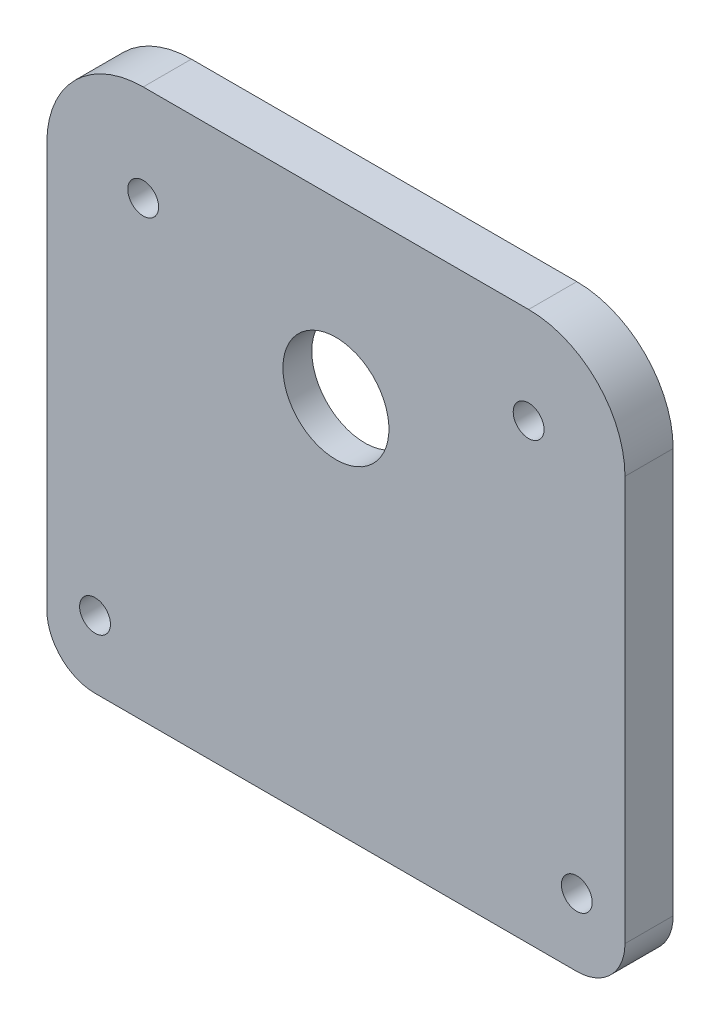
SolidWorks part; units mm, degrees
ref_plane "前视基准面" through (0, 0, 0) normal (0, 0, 1) x (1, 0, 0)
ref_plane "上视基准面" through (0, 0, 0) normal (0, 1, 0) x (1, 0, 0)
ref_plane "右视基准面" through (0, 0, 0) normal (1, 0, 0) x (0, 0, -1)
other "Configuration Table"
sketch "草图1" plane through (0, 0, 0) normal (0, 0, 1) x (1, 0, 0)
  line L1 (-30, -25) -> (30, -25)
  line L2 (-30, -25) -> (-30, 25)
  line L3 (-30, 25) -> (30, 25)
  line L4 (30, -25) -> (30, 25)
  line L5 (-30, -25) -> (30, 25) construction
  line L6 (-30, 25) -> (30, -25) construction
  circle A0 centre (0, 0) radius 15
  point P0 (0, 0)
  dimension "D3" = 30
  dimension "D1" = 60
  dimension "D2" = 50
extrude "凸台-拉伸5" add sketch "草图1" along normal blind 5
sketch "草图4" plane through (0, 0, 5) normal (0, 0, 1) x (1, 0, 0)
  line L1 (-30, -25) -> (30, -25)
  line L2 (-30, -25) -> (-30, 25)
  line L3 (-30, 25) -> (30, 25)
  line L4 (30, -25) -> (30, 25)
  line L5 (-30, -25) -> (30, 25) construction
  line L6 (-30, 25) -> (30, -25) construction
  circle A0 centre (0, 0) radius 5.5
  dimension "D1" = 11
extrude "凸台-拉伸6" add sketch "草图4" along normal blind 5
sketch "草图5" plane through (0, 0, 0) normal (0, 0, -1) x (-1, 0, 0)
  circle A0 centre (-20, 22) radius 1.6
  circle A1 centre (-25, -18) radius 1.6
  circle A2 centre (20, 22) radius 1.6
  circle A3 centre (25, -18) radius 1.6
extrude "切除-拉伸1" cut sketch "草图5" against normal blind 10
sketch "草图6" plane through (0, 25, 0) normal (0, 1, 0) x (1, 0, 0)
  line L1 (-30, -10) -> (30, -10)
  line L2 (-30, -10) -> (-30, 0)
  line L3 (-30, 0) -> (30, 0)
  line L4 (30, -10) -> (30, 0)
extrude "凸台-拉伸7" add sketch "草图6" along normal blind 7
fillet "圆角3" radius 10 1 edges at (-30, 32, 5)
fillet "圆角5" radius 10 1 edges at (30, 32, 5)
fillet "圆角6" radius 5 1 edges at (-30, -25, 5)
fillet "圆角7" radius 5 1 edges at (30, -25, 5)
sketch "草图7" plane through (0, 0, 0) normal (0, 0, -1) x (-1, 0, 0)
  line L1 (-30.7675, 32.3093) -> (32.1624, 32.3093)
  line L2 (-30.7675, 32.3093) -> (-30.7675, -27.2943)
  line L3 (-30.7675, -27.2943) -> (32.1624, -27.2943)
  line L4 (32.1624, 32.3093) -> (32.1624, -27.2943)
extrude "切除-拉伸2" cut sketch "草图7" against normal blind 5
sketch "草图8" plane through (0, 0, 5) normal (0, 0, -1) x (-1, 0, 0)
  circle A0 centre (0, 0) radius 15
  dimension "D1" = 30
extrude "切除-拉伸3" cut sketch "草图8" against normal blind 2
sketch "草图9" plane through (0, 0, 5) normal (0, 0, -1) x (-1, 0, 0)
  line L0 (0, 0) -> (0, 14)
  line L1 (-15, 14) -> (-15, 0)
  line L2 (15, 14) -> (15, 0)
  circle A0 centre (0, 14) radius 15
  circle A1 centre (0, 0) radius 15 construction
  circle A2 centre (0, 0) radius 15 construction
  circle M2 centre (0, 0) radius 15
  dimension "D2" = 30
  dimension "D1" = 14
extrude "切除-拉伸4" cut sketch "草图9" against normal blind 2 contours A0 M2 | A0 L1 M2 | A0 L2 M2
sketch "草图10" plane through (0, 0, 7) normal (0, 0, -1) x (-1, 0, 0)
  circle A0 centre (0, 14) radius 5.5
  dimension "D1" = 11
extrude "切除-拉伸6" cut sketch "草图10" against normal through all
sketch "草图11" plane through (0, 0, 7) normal (0, 0, -1) x (-1, 0, 0)
  circle A0 centre (0, 0) radius 5.5
extrude "凸台-拉伸8" add sketch "草图11" against normal blind 3
sketch "草图12" plane through (0, 0, 7) normal (0, 0, -1) x (-1, 0, 0)
  line L0 (-15, 14) -> (-15, 0)
  line L1 (15, 14) -> (15, 0)
  circle A0 centre (0, 0) radius 15
  circle A1 centre (0, 14) radius 15
  arc M2 (-15, 0) -> (15, 0) centre (0, 0) ccw
  line M3 (15, 0) -> (15, 14)
  line M5 (-15, 14) -> (-15, 0)
extrude "凸台-拉伸9" add sketch "草图12" along normal blind 2 contours A1 A0 M2 | A1 A0 M5 | A1 A0 M3
